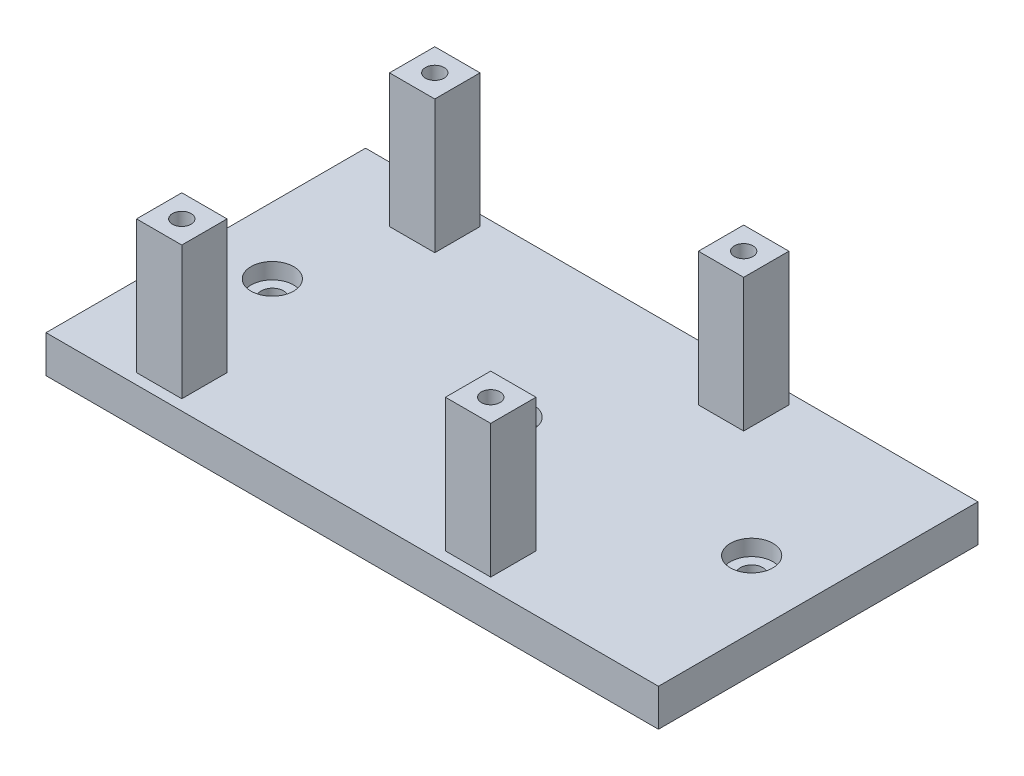
SolidWorks part; units mm, degrees
ref_plane "Front Plane" through (0, 0, 0) normal (0, 0, 1) x (1, 0, 0)
ref_plane "Top Plane" through (0, 0, 0) normal (0, 1, 0) x (1, 0, 0)
ref_plane "Right Plane" through (0, 0, 0) normal (1, 0, 0) x (0, 0, -1)
sketch "Sketch1" plane through (0, 0, 0) normal (0, 1, 0) x (1, 0, 0)
  line L0 (0, 0) -> (0, 60)
  line L1 (0, 0) -> (115, 0)
  line L2 (0, 60) -> (115, 60)
  line L3 (115, 60) -> (115, 0)
  line L4 (57.5, 60) -> (57.5, 0) construction
  line L5 (115, 30) -> (0, 30) construction
  line L6 (0, 30) -> (12.5, 30) construction
  circle A0 centre (57.5, 30) radius 2.1
  circle A3 centre (12.5, 30) radius 2.1
  circle A5 centre (102.5, 30) radius 2.1
extrude "Boss-Extrude2" add sketch "Sketch1" along normal blind 7
sketch "Sketch2" plane through (0, 7, 0) normal (0, 1, 0) x (1, 0, 0)
  circle A0 centre (12.5, 30) radius 4
  circle A1 centre (57.5, 30) radius 4
  circle A2 centre (102.5, 30) radius 4
extrude "Cut-Extrude1" cut sketch "Sketch2" against normal blind 3
sketch "Sketch5" plane through (0, 7, 0) normal (0, 1, 0) x (1, 0, 0)
  line L0 (57.5, 30) -> (57.5, 58) construction
  line L1 (57.5, 30) -> (57.5, 2) construction
  line L2 (57.5, 58) -> (100, 58) construction
  line L3 (100, 58) -> (100, 2) construction
  line L4 (100, 2) -> (57.5, 2) construction
  line L5 (57.5, 2) -> (15, 2) construction
  line L6 (15, 2) -> (15, 58) construction
  line L7 (15, 58) -> (57.5, 58) construction
  line L8 (15, 58) -> (23.5, 58)
  line L9 (23.5, 58) -> (23.5, 49.5)
  line L10 (23.5, 49.5) -> (15, 49.5)
  line L11 (15, 49.5) -> (15, 58)
  line L12 (15, 2) -> (23.5, 2)
  line L13 (19.25, 53.75) -> (77.25, 53.75) construction
  line L14 (77.25, 58) -> (81.5, 58)
  line L15 (81.5, 58) -> (81.5, 49.5)
  line L16 (81.5, 49.5) -> (73, 49.5)
  line L17 (73, 49.5) -> (73, 58)
  line L18 (73, 58) -> (77.25, 58)
  line L19 (57.5, 30) -> (15, 30) construction
  line L20 (73, 10.5) -> (73, 2)
  line L21 (81.5, 10.5) -> (73, 10.5)
  line L22 (81.5, 2) -> (81.5, 10.5)
  line L23 (77.25, 2) -> (81.5, 2)
  line L24 (73, 2) -> (77.25, 2)
  line L25 (23.5, 10.5) -> (15, 10.5)
  line L26 (23.5, 2) -> (23.5, 10.5)
  line L27 (15, 2) -> (23.5, 2)
  line L28 (15, 10.5) -> (15, 2)
  point P13 (0, 0)
extrude "Boss-Extrude3" add sketch "Sketch5" along normal blind 25 contours L11 L10 L9 L8 | L25 L28 L12 L26 | L18 L17 L16 L15 L14 | L20 L24 L23 L22 L21
sketch "Sketch6" plane through (0, 32, 0) normal (0, 1, 0) x (1, 0, 0)
  circle A0 centre (19.25, 53.75) radius 1.75
  circle A1 centre (77.25, 53.75) radius 1.75
  circle A2 centre (19.25, 6.25) radius 1.75
  circle A3 centre (77.25, 6.25) radius 1.75
extrude "Cut-Extrude2" cut sketch "Sketch6" against normal blind 10
